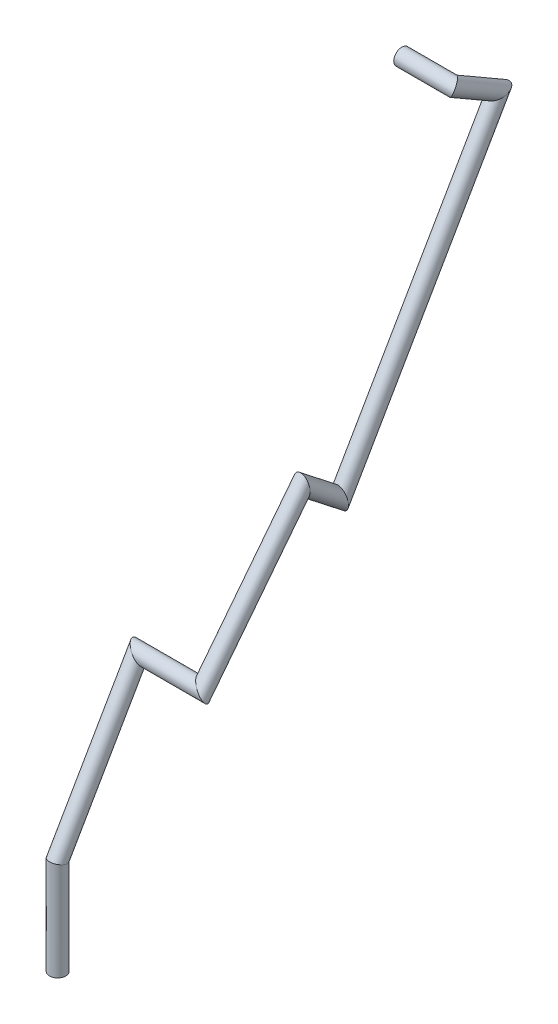
SolidWorks part; units mm, degrees
ref_plane "Front Plane" through (0, 0, 0) normal (0, 0, 1) x (1, 0, 0)
ref_plane "Top Plane" through (0, 0, 0) normal (0, 1, 0) x (1, 0, 0)
ref_plane "Right Plane" through (0, 0, 0) normal (1, 0, 0) x (0, 0, -1)
sketch3d "3DSketch1"
  line L0 (0, 0, 0) -> (0, 30, 0)
  line L1 (0, 30, 0) -> (0, 73.3013, -25)
  line L2 (0, 73.3013, -25) -> (20, 73.3013, -25)
  line L3 (0, 73.3013, -25) -> (0, 137.4756, -75.1385) construction
  line L4 (20, 73.3013, -25) -> (20, 112.7018, -55.7831)
  line L5 (20, 112.7018, -55.7831) -> (20, 103.4669, -67.6032)
  line L6 (20, 103.4669, -67.6032) -> (20, 188.3374, -116.6032)
  line L7 (20, 112.7018, -55.7831) -> (53.8812, 112.7018, -55.7831) construction
  line L8 (20, 188.3374, -116.6032) -> (20, 196.3374, -102.7468)
  line L9 (20, 196.3374, -102.7468) -> (3.9785, 196.3374, -102.7468)
  dimension "D1" = 30
  dimension "D2" = 150
  dimension "D3" = 50
  dimension "D4" = 20
  dimension "D5" = 172
  dimension "D6" = 50
  dimension "D7" = 15
  dimension "D8" = 98
  dimension "D9" = 16
  dimension "D10" = 90
  dimension "D11" = 90
sweep "Sweep1" add path "3DSketch1" circular profile diameter 5 parameters "D3"=5
